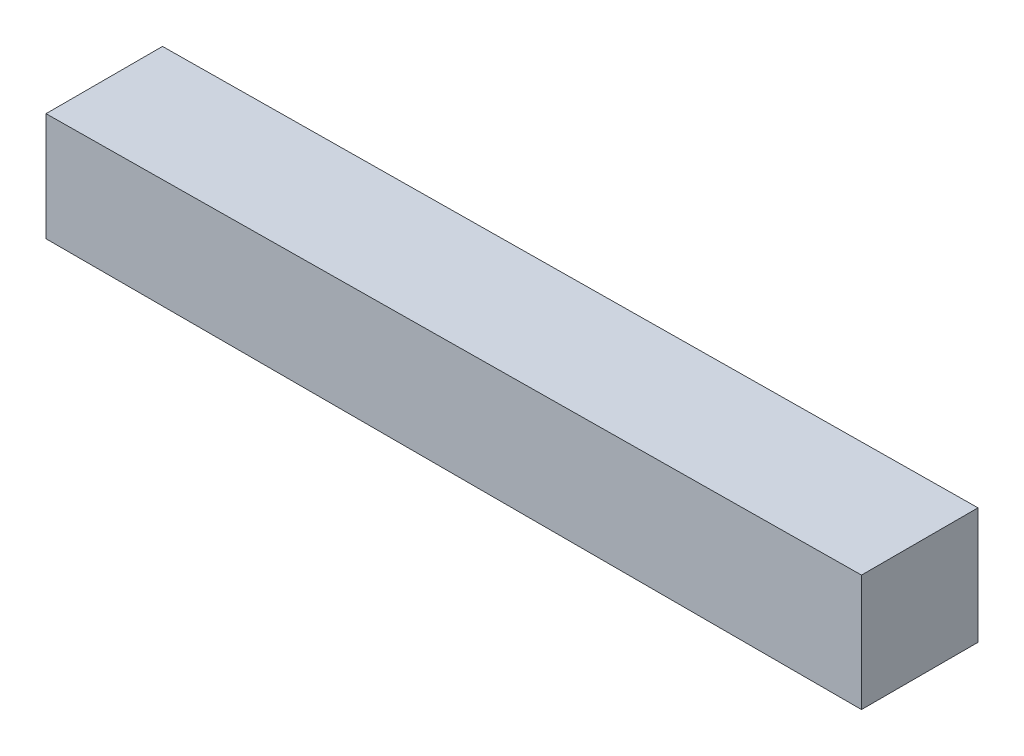
SolidWorks part; units mm, degrees
ref_plane "Front Plane" through (0, 0, 0) normal (0, 0, 1) x (1, 0, 0)
ref_plane "Top Plane" through (0, 0, 0) normal (0, 1, 0) x (1, 0, 0)
ref_plane "Right Plane" through (0, 0, 0) normal (1, 0, 0) x (0, 0, -1)
sketch "Sketch1" plane through (0, 0, 0) normal (0, 0, 1) x (1, 0, 0)
  line L0 (17.5, 2.5) -> (17.5, -2.5)
  line L1 (17.5, -2.5) -> (-17.5, -2.5)
  line L2 (-17.5, -2.5) -> (-17.5, 2.15)
  line L3 (-17.5, 2.15) -> (17.5, 2.5)
  point P5 (17.5, 0)
  point P6 (0, -2.5)
  dimension "D1" = 5
  dimension "D2" = 35
  dimension "D3" = 4.65
extrude "Boss-Extrude1" add sketch "Sketch1" along normal mid plane 5
